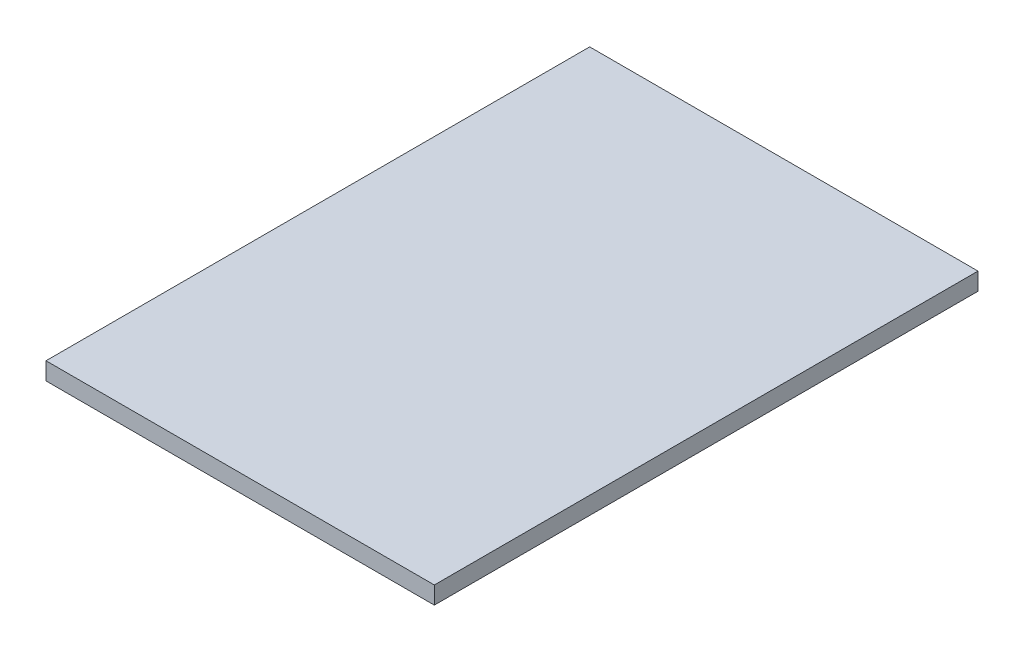
SolidWorks part; units mm, degrees
ref_plane "Front Plane" through (0, 0, 0) normal (0, 0, 1) x (1, 0, 0)
ref_plane "Top Plane" through (0, 0, 0) normal (0, 1, 0) x (1, 0, 0)
ref_plane "Right Plane" through (0, 0, 0) normal (1, 0, 0) x (0, 0, -1)
sketch "Sketch1" plane through (0, 0, 0) normal (0, 1, 0) x (1, 0, 0)
  line L1 (-10, -14) -> (10, -14)
  line L2 (-10, -14) -> (-10, 14)
  line L3 (-10, 14) -> (10, 14)
  line L4 (10, -14) -> (10, 14)
  line L5 (-10, -14) -> (10, 14) construction
  line L6 (-10, 14) -> (10, -14) construction
  point P0 (0, 0)
  dimension "D1" = 20
  dimension "D2" = 28
extrude "Boss-Extrude1" add sketch "Sketch1" along normal blind 0.9
